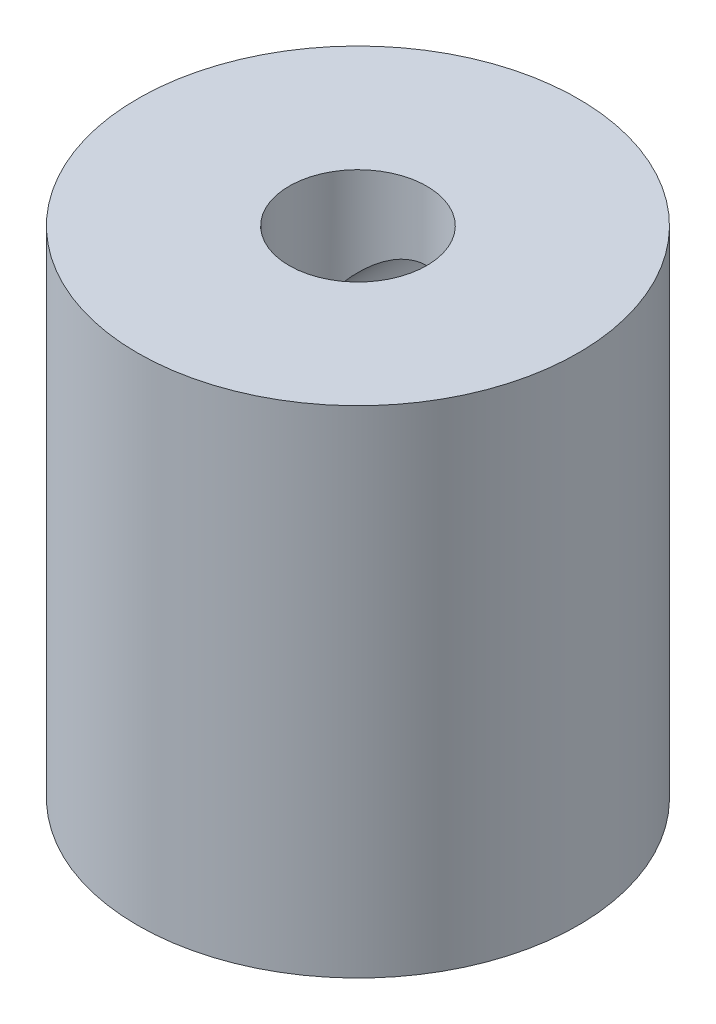
SolidWorks part; units mm, degrees
ref_plane "Plano frontal" through (0, 0, 0) normal (0, 0, 1) x (1, 0, 0)
ref_plane "Plano superior" through (0, 0, 0) normal (0, 1, 0) x (1, 0, 0)
ref_plane "Plano direito" through (0, 0, 0) normal (1, 0, 0) x (0, 0, -1)
sketch "Esboço1" plane through (0, 0, 0) normal (0, 1, 0) x (1, 0, 0)
  circle A0 centre (0, 0) radius 4
  circle A1 centre (0, 0) radius 1.25
  dimension "D1" = 8
  dimension "D2" = 2.5
extrude "Ressalto-extrusão1" add sketch "Esboço1" along normal blind 9
sketch "Esboço2" plane through (0, 0, 0) normal (0, 0, 1) x (1, 0, 0)
  line L0 (0, -0.2628) -> (0, 9.2628) construction
  line L1 (1.25, 9) -> (-1.25, 9) construction
  line L2 (-4, 0) -> (4, 0) construction
  circle A0 centre (0, 6.5) radius 1.25
  circle A1 centre (0, 2.5) radius 1.25
  dimension "D1" = 2.5
  dimension "D2" = 2.5
  dimension "D3" = 2.5
  dimension "D4" = 2.5
extrude "Corte-extrusão1" cut sketch "Esboço2" against normal blind 9
